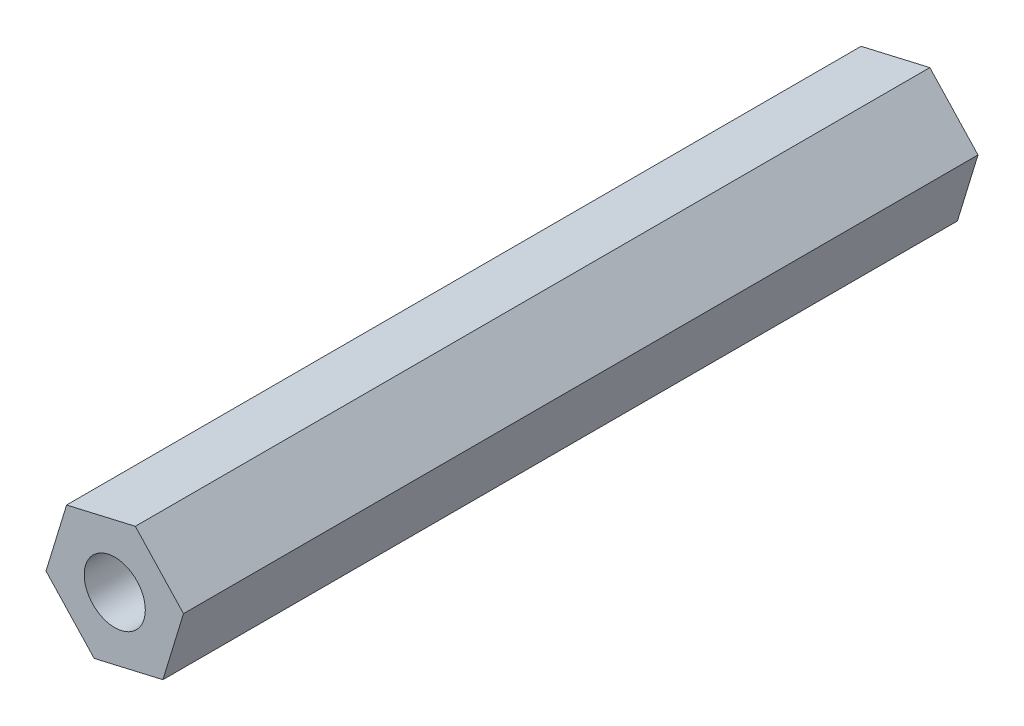
SolidWorks part; units mm, degrees
ref_plane "Front Plane" through (0, 0, 0) normal (0, 0, 1) x (1, 0, 0)
ref_plane "Top Plane" through (0, 0, 0) normal (0, 1, 0) x (1, 0, 0)
ref_plane "Right Plane" through (0, 0, 0) normal (1, 0, 0) x (0, 0, -1)
sketch "Sketch1" plane through (0, 0, 0) normal (0, 0, 1) x (1, 0, 0)
  line L1 (5.0043, -5.3591) -> (7.1433, 1.6543)
  line L2 (7.1433, 1.6543) -> (2.139, 7.0134)
  line L3 (2.139, 7.0134) -> (-5.0043, 5.3591)
  line L4 (-5.0043, 5.3591) -> (-7.1433, -1.6543)
  line L5 (-7.1433, -1.6543) -> (-2.139, -7.0134)
  line L6 (-2.139, -7.0134) -> (5.0043, -5.3591)
  circle A0 centre (0, 0) radius 6.35 construction
  dimension "D1" = 12.7
extrude "Boss-Extrude1" add sketch "Sketch1" along normal blind 82.55
sketch "Sketch2" plane through (0, 0, 82.55) normal (0, 0, 1) x (1, 0, 0)
  circle A0 centre (0, 0) radius 3.175
  dimension "D1" = 6.35
extrude "Cut-Extrude1" cut sketch "Sketch2" against normal blind 127
